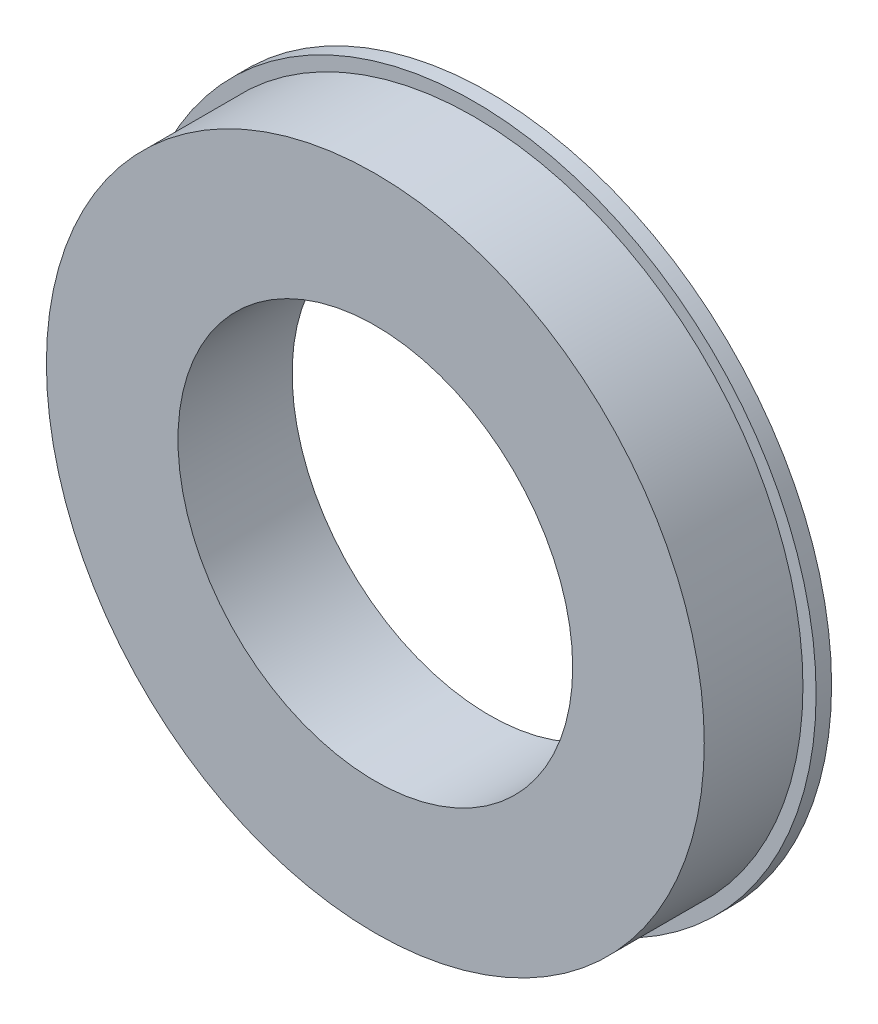
SolidWorks part; units mm, degrees
ref_plane "Front Plane" through (0, 0, 0) normal (0, 0, 1) x (1, 0, 0)
ref_plane "Top Plane" through (0, 0, 0) normal (0, 1, 0) x (1, 0, 0)
ref_plane "Right Plane" through (0, 0, 0) normal (1, 0, 0) x (0, 0, -1)
sketch "Sketch1" plane through (0, 0, 0) normal (1, 0, 0) x (0, 0, -1)
  line L0 (-105.8752, 0) -> (147.1188, 0) construction
  line L2 (0, 38.1) -> (22.04, 38.1)
  line L3 (0, 38.1) -> (0, 63.5)
  line L4 (0, 63.5) -> (22.04, 63.5)
  line L5 (22.04, 38.1) -> (22.04, 63.5)
  line L6 (22.04, 63.5) -> (19.05, 63.5)
  line L7 (22.04, 63.5) -> (22.04, 66.04)
  line L8 (22.04, 66.04) -> (19.05, 66.04)
  line L9 (19.05, 63.5) -> (19.05, 66.04)
  dimension "D1" = 76.2
  dimension "D2" = 127
  dimension "D3" = 2.54
  dimension "D4" = 19.05
  dimension "D5" = 22.04
revolve "Revolve1" add sketch "Sketch1" angle 360 about L0
